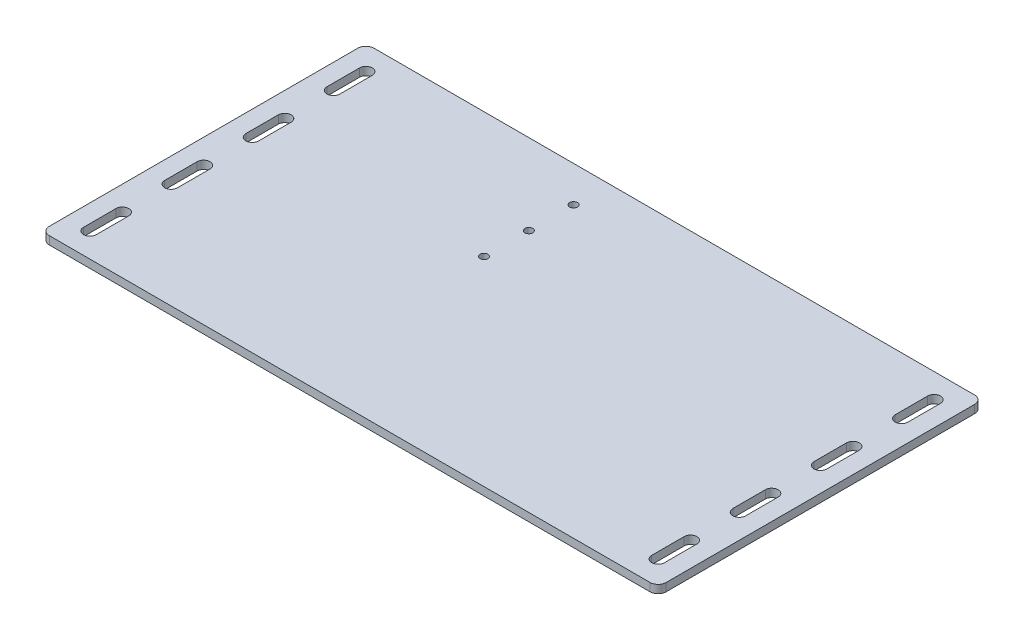
SolidWorks part; units mm, degrees
material "6061-T6 (SS)"
ref_plane "Front Plane" through (0, 0, 0) normal (0, 0, 1) x (1, 0, 0)
ref_plane "Top Plane" through (0, 0, 0) normal (0, 1, 0) x (1, 0, 0)
ref_plane "Right Plane" through (0, 0, 0) normal (1, 0, 0) x (0, 0, -1)
sketch "Sketch1" plane through (0, 0, 0) normal (0, 1, 0) x (1, 0, 0)
  line L1 (-241.3, 127) -> (241.3, 127)
  line L2 (-241.3, 127) -> (-241.3, -127)
  line L3 (-241.3, -127) -> (241.3, -127)
  line L4 (241.3, 127) -> (241.3, -127)
  line L5 (-241.3, 127) -> (241.3, -127) construction
  line L6 (-241.3, -127) -> (241.3, 127) construction
  point P0 (0, 0)
  dimension "D1" = 482.6
  dimension "D2" = 254
extrude "Boss-Extrude1" add sketch "Sketch1" along normal mid plane 6.35
fillet "Fillet1" radius 6.35 4 edges at (-241.3, 0, 127) (-241.3, 0, -127) (241.3, 0, -127) (241.3, 0, 127)
sketch "Sketch2" plane through (0, 3.175, 0) normal (0, 1, 0) x (1, 0, 0)
  line L0 (222.25, 127) -> (222.25, -127) construction
  line L1 (234.95, 127) -> (-234.95, 127) construction
  line L2 (-234.95, -127) -> (234.95, -127) construction
  line L3 (0, 0) -> (222.25, 0) construction
  line L4 (111.125, 0) -> (111.125, -127) construction
  line L5 (111.125, -63.5) -> (222.25, -63.5) construction
  line L6 (166.6875, -63.5) -> (166.6875, -127) construction
  line L7 (222.25, -82.55) -> (222.25, -107.95) construction
  line L8 (227.25, -82.55) -> (227.25, -107.95)
  line L9 (217.25, -82.55) -> (217.25, -107.95)
  line L10 (222.25, 44.45) -> (222.25, 19.05) construction
  line L13 (222.25, -44.45) -> (222.25, -19.05) construction
  line L14 (227.25, -44.45) -> (227.25, -19.05)
  line L15 (217.25, -44.45) -> (217.25, -19.05)
  line L16 (227.25, 44.45) -> (227.25, 19.05)
  line L17 (217.25, 44.45) -> (217.25, 19.05)
  line L18 (222.25, 82.55) -> (222.25, 107.95) construction
  line L19 (227.25, 82.55) -> (227.25, 107.95)
  line L20 (217.25, 82.55) -> (217.25, 107.95)
  line L21 (0, -55) -> (0, 55) construction
  line L22 (-222.25, 82.55) -> (-222.25, 107.95) construction
  line L23 (-227.25, 82.55) -> (-227.25, 107.95)
  line L24 (-217.25, 82.55) -> (-217.25, 107.95)
  line L25 (-222.25, 44.45) -> (-222.25, 19.05) construction
  line L26 (-227.25, 44.45) -> (-227.25, 19.05)
  line L27 (-217.25, 44.45) -> (-217.25, 19.05)
  line L28 (-222.25, -44.45) -> (-222.25, -19.05) construction
  line L29 (-227.25, -44.45) -> (-227.25, -19.05)
  line L30 (-217.25, -44.45) -> (-217.25, -19.05)
  line L31 (-222.25, -82.55) -> (-222.25, -107.95) construction
  line L32 (-227.25, -82.55) -> (-227.25, -107.95)
  line L33 (-217.25, -82.55) -> (-217.25, -107.95)
  arc A0 (227.25, -82.55) -> (217.25, -82.55) centre (222.25, -82.55) ccw
  arc A1 (217.25, -107.95) -> (227.25, -107.95) centre (222.25, -107.95) ccw
  arc A4 (227.25, -44.45) -> (217.25, -44.45) centre (222.25, -44.45) cw
  arc A5 (217.25, -19.05) -> (227.25, -19.05) centre (222.25, -19.05) cw
  arc A6 (227.25, 44.45) -> (217.25, 44.45) centre (222.25, 44.45) ccw
  arc A7 (217.25, 19.05) -> (227.25, 19.05) centre (222.25, 19.05) ccw
  arc A8 (227.25, 82.55) -> (217.25, 82.55) centre (222.25, 82.55) cw
  arc A9 (217.25, 107.95) -> (227.25, 107.95) centre (222.25, 107.95) cw
  arc A10 (-227.25, 82.55) -> (-217.25, 82.55) centre (-222.25, 82.55) ccw
  arc A11 (-217.25, 107.95) -> (-227.25, 107.95) centre (-222.25, 107.95) ccw
  arc A12 (-227.25, 44.45) -> (-217.25, 44.45) centre (-222.25, 44.45) cw
  arc A13 (-217.25, 19.05) -> (-227.25, 19.05) centre (-222.25, 19.05) cw
  arc A14 (-227.25, -44.45) -> (-217.25, -44.45) centre (-222.25, -44.45) ccw
  arc A15 (-217.25, -19.05) -> (-227.25, -19.05) centre (-222.25, -19.05) ccw
  arc A16 (-227.25, -82.55) -> (-217.25, -82.55) centre (-222.25, -82.55) cw
  arc A17 (-217.25, -107.95) -> (-227.25, -107.95) centre (-222.25, -107.95) cw
  point P17 (222.25, -95.25)
  point P23 (166.6875, -95.25)
  point P26 (222.25, 31.75)
  point P33 (222.25, -31.75)
  point P40 (222.25, 95.25)
  point P49 (-222.25, 95.25)
  point P56 (-222.25, 31.75)
  point P63 (-222.25, -31.75)
  point P70 (-222.25, -95.25)
  dimension "D2" = 5
  dimension "D1" = 222.25
  dimension "D3" = 25.4
extrude "Cut-Extrude1" cut sketch "Sketch2" against normal up to next
sketch "Sketch3" plane through (0, 3.175, 0) normal (0, 1, 0) x (1, 0, 0)
  circle A0 centre (-50.8, 98.956) radius 3.05 construction
  circle A1 centre (-50.8, 98.956) radius 3.05
  circle A2 centre (-50.8, 63.956) radius 3.05 construction
  circle A3 centre (-50.8, 63.956) radius 3.05
  circle A4 centre (-50.8, 28.956) radius 3.05 construction
  circle A5 centre (-50.8, 28.956) radius 3.05
extrude "Cut-Extrude2" cut sketch "Sketch3" against normal through all
equation "\"width\"=482.6"
equation "\"height\"=254"
equation "\"D1@Sketch1\"=\"width\""
equation "\"D2@Sketch1\"=\"height\""
